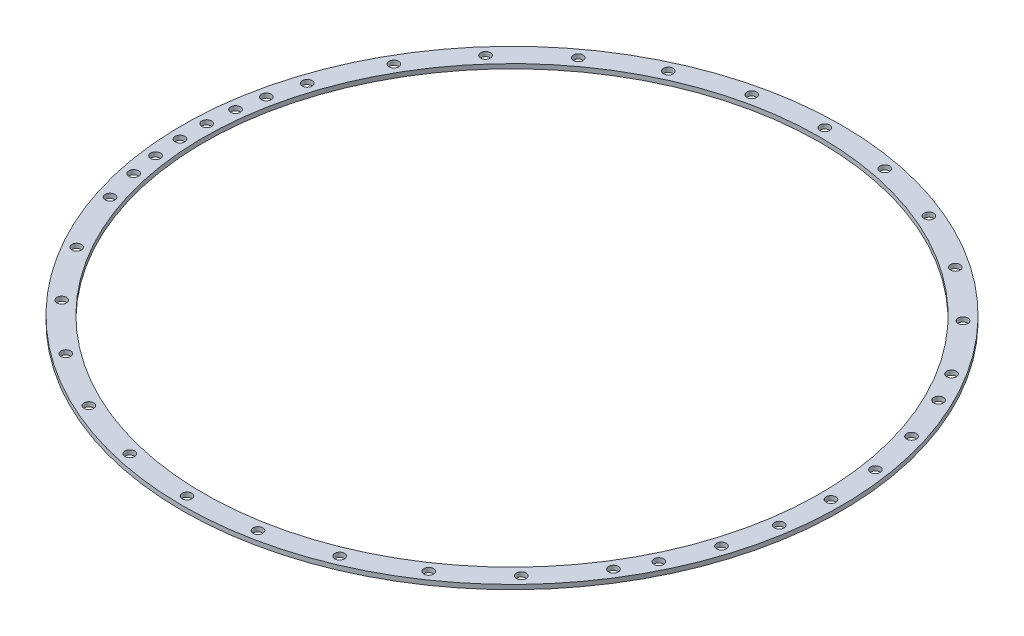
SolidWorks part; units mm, degrees
material "Hexcel AS4C (3000 Filaments)"
ref_plane "Front Plane" through (0, 0, 0) normal (0, 0, 1) x (1, 0, 0)
ref_plane "Top Plane" through (0, 0, 0) normal (0, 1, 0) x (1, 0, 0)
ref_plane "Right Plane" through (0, 0, 0) normal (1, 0, 0) x (0, 0, -1)
sketch "Sketch1" plane through (0, 0, 0) normal (0, 0, 1) x (1, 0, 0)
  line L0 (-102, 3.175) -> (-102, 4.675) construction
  line L1 (-109, 3.175) -> (-109, 4.675) construction
  line L2 (-102, 3.175) -> (-102, 4.675)
  line L3 (-109, 3.175) -> (-109, 4.675)
  line L4 (-109, 4.675) -> (-102, 4.675)
  line L5 (-102, 3.175) -> (-109, 3.175)
  line L6 (0, -200069.0475) -> (0, 200086.9028) construction
  line L7 (0, -200069.0475) -> (0, 200086.9028) construction
revolve "Revolve1" add sketch "Sketch1" angle 360 about L7
sketch "Sketch3" plane through (0, 4.675, 0) normal (0, 1, 0) x (1, 0, 0)
  circle A1 centre (-103.1946, -21.9347) radius 1.6
  circle A2 centre (-103.1946, -21.9347) radius 1.6
  circle A3 centre (-105.4075, -4.4179) radius 1.6
  circle A4 centre (-105.4075, -4.4179) radius 1.6
  circle A5 centre (-104.6681, -13.2227) radius 1.6
  circle A6 centre (-104.6681, -13.2227) radius 1.6
  circle A7 centre (-100.3365, 32.6013) radius 1.6
  circle A8 centre (-100.3365, 32.6013) radius 1.6
  circle A9 centre (104.2954, 15.8973) radius 1.6
  circle A10 centre (104.2954, 15.8973) radius 1.6
  circle A11 centre (100.709, 31.4316) radius 1.6
  circle A12 centre (100.709, 31.4316) radius 1.6
  circle A13 centre (94.8228, 46.2482) radius 1.6
  circle A14 centre (94.8228, 46.2482) radius 1.6
  circle A15 centre (-103.1946, 21.9347) radius 1.6
  circle A16 centre (-103.1946, 21.9347) radius 1.6
  circle A17 centre (-104.6681, 13.2227) radius 1.6
  circle A18 centre (-104.6681, 13.2227) radius 1.6
  circle A19 centre (-105.4075, 4.4179) radius 1.6
  circle A20 centre (-105.4075, 4.4179) radius 1.6
  circle A21 centre (89.4691, -55.9065) radius 1.6
  circle A22 centre (89.4691, -55.9065) radius 1.6
  circle A23 centre (-44.1306, 95.8266) radius 1.6
  circle A24 centre (-44.1306, 95.8266) radius 1.6
  circle A25 centre (-62.8211, 84.7571) radius 1.6
  circle A26 centre (-62.8211, 84.7571) radius 1.6
  circle A27 centre (-78.8482, 70.0943) radius 1.6
  circle A28 centre (-78.8482, 70.0943) radius 1.6
  circle A29 centre (-91.5326, 52.4598) radius 1.6
  circle A30 centre (-91.5326, 52.4598) radius 1.6
  circle A31 centre (94.8228, -46.2482) radius 1.6
  circle A32 centre (94.8228, -46.2482) radius 1.6
  circle A33 centre (100.709, -31.4316) radius 1.6
  circle A34 centre (100.709, -31.4316) radius 1.6
  circle A35 centre (104.2954, -15.8973) radius 1.6
  circle A36 centre (104.2954, -15.8973) radius 1.6
  circle A37 centre (105.5, 0) radius 1.6
  circle A38 centre (105.5, 0) radius 1.6
  circle A39 centre (76.1225, -73.0453) radius 1.6
  circle A40 centre (76.1225, -73.0453) radius 1.6
  circle A41 centre (89.4691, 55.9065) radius 1.6
  circle A42 centre (89.4691, 55.9065) radius 1.6
  circle A43 centre (76.1225, 73.0453) radius 1.6
  circle A44 centre (76.1225, 73.0453) radius 1.6
  circle A45 centre (59.5488, 87.0873) radius 1.6
  circle A46 centre (59.5488, 87.0873) radius 1.6
  circle A47 centre (40.4504, 97.4372) radius 1.6
  circle A48 centre (40.4504, 97.4372) radius 1.6
  circle A49 centre (19.6372, 103.6563) radius 1.6
  circle A50 centre (19.6372, 103.6563) radius 1.6
  circle A51 centre (-2.0086, 105.4809) radius 1.6
  circle A52 centre (-2.0086, 105.4809) radius 1.6
  circle A53 centre (-23.5692, 102.8336) radius 1.6
  circle A54 centre (-23.5692, 102.8336) radius 1.6
  circle A55 centre (-91.5326, -52.4598) radius 1.6
  circle A56 centre (-91.5326, -52.4598) radius 1.6
  circle A57 centre (-62.8211, -84.7571) radius 1.6
  circle A58 centre (-62.8211, -84.7571) radius 1.6
  circle A59 centre (-44.1306, -95.8266) radius 1.6
  circle A60 centre (-44.1306, -95.8266) radius 1.6
  circle A61 centre (-23.5692, -102.8336) radius 1.6
  circle A62 centre (-23.5692, -102.8336) radius 1.6
  circle A63 centre (-2.0086, -105.4809) radius 1.6
  circle A64 centre (-2.0086, -105.4809) radius 1.6
  circle A65 centre (19.6372, -103.6563) radius 1.6
  circle A66 centre (19.6372, -103.6563) radius 1.6
  circle A67 centre (40.4504, -97.4372) radius 1.6
  circle A68 centre (40.4504, -97.4372) radius 1.6
  circle A69 centre (59.5488, -87.0873) radius 1.6
  circle A70 centre (59.5488, -87.0873) radius 1.6
  circle A71 centre (-78.8482, -70.0943) radius 1.6
  circle A72 centre (-78.8482, -70.0943) radius 1.6
  circle A73 centre (-100.3365, -32.6013) radius 1.6
  circle A74 centre (-100.3365, -32.6013) radius 1.6
  dimension "D1" = 0
  dimension "D2" = 0
  dimension "D3" = 0
  dimension "D4" = 0
  dimension "D5" = 0
  dimension "D6" = 0
  dimension "D7" = 0
  dimension "D8" = 0
  dimension "D9" = 0
  dimension "D10" = 0
  dimension "D11" = 0
  dimension "D12" = 0
  dimension "D13" = 0
  dimension "D14" = 0
  dimension "D15" = 0
  dimension "D16" = 0
  dimension "D17" = 0
  dimension "D18" = 0
  dimension "D19" = 0
  dimension "D20" = 0
  dimension "D21" = 0
  dimension "D22" = 0
  dimension "D23" = 0
  dimension "D24" = 0
  dimension "D25" = 0
  dimension "D26" = 0
  dimension "D27" = 0
  dimension "D28" = 0
  dimension "D29" = 0
  dimension "D30" = 0
  dimension "D31" = 0
  dimension "D32" = 0
  dimension "D33" = 0
  dimension "D34" = 0
  dimension "D35" = 0
  dimension "D36" = 0
  dimension "D37" = 0
extrude "Cut-Extrude2" cut sketch "Sketch3" against normal through all
